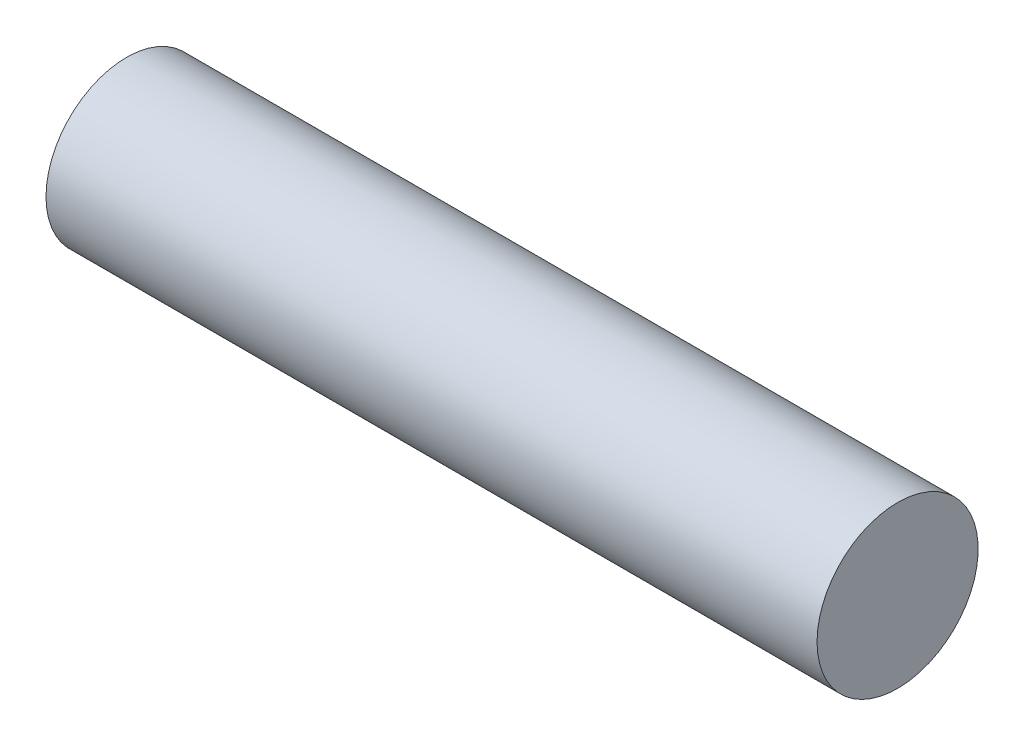
SolidWorks part; units mm, degrees
material "AISI 1020"
ref_plane "Plano frontal" through (0, 0, 0) normal (0, 0, 1) x (1, 0, 0)
ref_plane "Plano superior" through (0, 0, 0) normal (0, 1, 0) x (1, 0, 0)
ref_plane "Plano direito" through (0, 0, 0) normal (1, 0, 0) x (0, 0, -1)
sketch "Sketch1" plane through (0, 0, 0) normal (0, 1, 0) x (1, 0, 0)
  line L0 (33.5, -3.5) -> (-33.5, -3.5) construction
  line L1 (-33.5, -7) -> (33.5, -7)
  line L2 (-33.5, -7) -> (-33.5, 0)
  line L3 (-33.5, 0) -> (33.5, 0)
  line L4 (33.5, -7) -> (33.5, 0)
  line L5 (0, 0) -> (0, -7) construction
  point P0 (0, 0)
  dimension "D1" = 67
  dimension "D2" = 7
revolve "Revolve2" add sketch "Sketch1" angle 360 about L3
